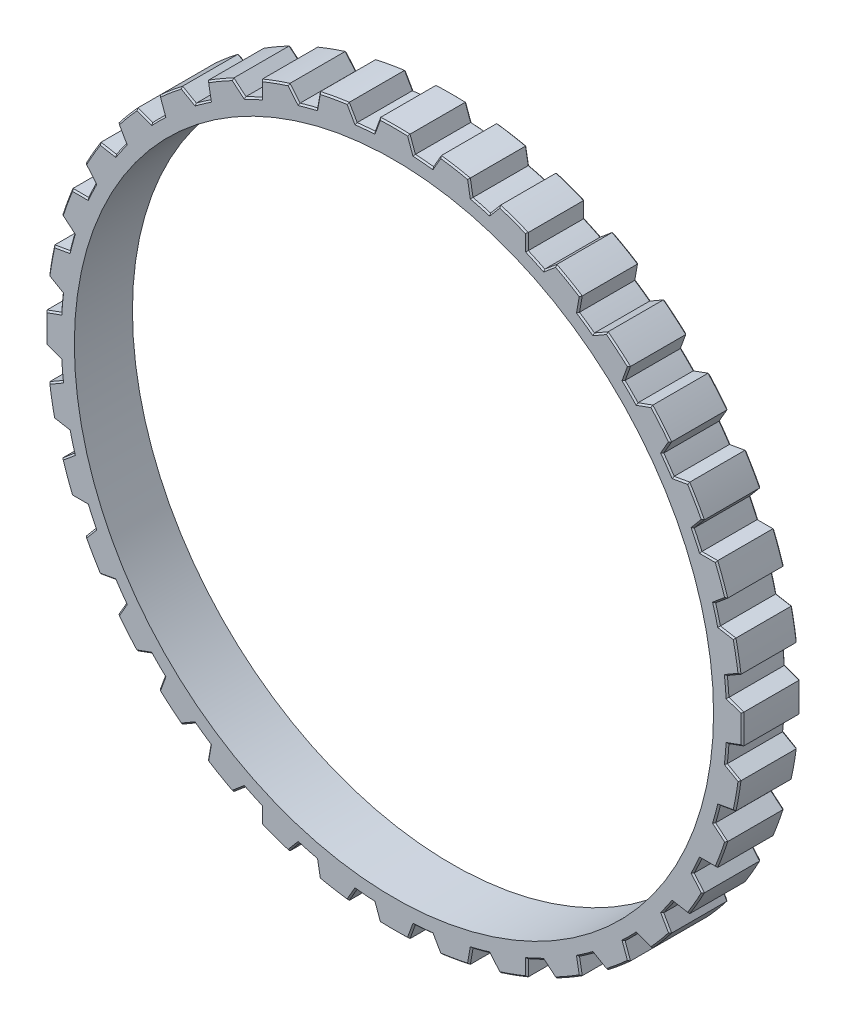
SolidWorks part; units mm, degrees
ref_plane "Płaszczyzna przednia" through (0, 0, 0) normal (0, 0, 1) x (1, 0, 0)
ref_plane "Płaszczyzna górna" through (0, 0, 0) normal (0, 1, 0) x (1, 0, 0)
ref_plane "Płaszczyzna prawa" through (0, 0, 0) normal (1, 0, 0) x (0, 0, -1)
sketch "Szkic1" plane through (0, 0, 0) normal (0, 0, 1) x (1, 0, 0)
  circle A0 centre (0, 0) radius 120
  circle A1 centre (0, 0) radius 110
  dimension "D1" = 240
  dimension "D2" = 220
extrude "Dodanie-wyciągnięcie1" add sketch "Szkic1" along normal blind 20
sketch "Szkic2" plane through (0, 0, 0) normal (0, 0, -1) x (-1, 0, 0)
  line L0 (0, 115) -> (0, 132.2478)
  line L1 (15.8574, 118.9476) -> (13.1432, 114.2465)
  line L2 (-5.0385, 119.8942) -> (-6.8952, 114.7931)
  line L3 (5.0385, 119.8942) -> (6.8952, 114.7931)
  line L4 (25.7814, 117.1978) -> (26.724, 111.8518)
  line L5 (36.2716, 114.3869) -> (32.7822, 110.2285)
  line L6 (45.7409, 110.9404) -> (45.7409, 105.512)
  line L7 (55.5836, 106.3507) -> (51.4252, 102.8613)
  line L8 (64.3106, 101.3121) -> (63.3679, 95.9662)
  line L9 (73.2068, 95.083) -> (68.5056, 92.3687)
  line L10 (80.9262, 88.6056) -> (79.0696, 83.5045)
  line L11 (88.6056, 80.9262) -> (83.5045, 79.0696)
  line L12 (95.083, 73.2068) -> (92.3687, 68.5056)
  line L13 (101.3121, 64.3106) -> (95.9662, 63.3679)
  line L14 (106.3507, 55.5836) -> (102.8613, 51.4252)
  line L15 (110.9404, 45.7409) -> (105.512, 45.7409)
  line L16 (114.3869, 36.2716) -> (110.2285, 32.7822)
  line L17 (117.1978, 25.7814) -> (111.8518, 26.724)
  line L18 (118.9476, 15.8574) -> (114.2465, 13.1432)
  line L19 (119.8942, 5.0385) -> (114.7931, 6.8952)
  line L20 (119.8942, -5.0385) -> (114.7931, -6.8952)
  line L21 (118.9476, -15.8574) -> (114.2465, -13.1432)
  line L22 (117.1978, -25.7814) -> (111.8518, -26.724)
  line L23 (114.3869, -36.2716) -> (110.2285, -32.7822)
  line L24 (110.9404, -45.7409) -> (105.512, -45.7409)
  line L25 (106.3507, -55.5836) -> (102.8613, -51.4252)
  line L26 (101.3121, -64.3106) -> (95.9662, -63.3679)
  line L27 (95.083, -73.2068) -> (92.3687, -68.5056)
  line L28 (88.6056, -80.9262) -> (83.5045, -79.0696)
  line L29 (80.9262, -88.6056) -> (79.0696, -83.5045)
  line L30 (73.2068, -95.083) -> (68.5056, -92.3687)
  line L31 (64.3106, -101.3121) -> (63.3679, -95.9662)
  line L32 (55.5836, -106.3507) -> (51.4252, -102.8613)
  line L33 (45.7409, -110.9404) -> (45.7409, -105.512)
  line L34 (36.2716, -114.3869) -> (32.7822, -110.2285)
  line L35 (25.7814, -117.1978) -> (26.724, -111.8518)
  line L36 (15.8574, -118.9476) -> (13.1432, -114.2465)
  line L37 (5.0385, -119.8942) -> (6.8952, -114.7931)
  line L38 (-5.0385, -119.8942) -> (-6.8952, -114.7931)
  line L39 (-15.8574, -118.9476) -> (-13.1432, -114.2465)
  line L40 (-25.7814, -117.1978) -> (-26.724, -111.8518)
  line L41 (-36.2716, -114.3869) -> (-32.7822, -110.2285)
  line L42 (-45.7409, -110.9404) -> (-45.7409, -105.512)
  line L43 (-55.5836, -106.3507) -> (-51.4252, -102.8613)
  line L44 (-64.3106, -101.3121) -> (-63.3679, -95.9662)
  line L45 (-73.2068, -95.083) -> (-68.5056, -92.3687)
  line L46 (-80.9262, -88.6056) -> (-79.0696, -83.5045)
  line L47 (-88.6056, -80.9262) -> (-83.5045, -79.0696)
  line L48 (-95.083, -73.2068) -> (-92.3687, -68.5056)
  line L49 (-101.3121, -64.3106) -> (-95.9662, -63.3679)
  line L50 (-106.3507, -55.5836) -> (-102.8613, -51.4252)
  line L51 (-110.9404, -45.7409) -> (-105.512, -45.7409)
  line L52 (-114.3869, -36.2716) -> (-110.2285, -32.7822)
  line L53 (-117.1978, -25.7814) -> (-111.8518, -26.724)
  line L54 (-118.9476, -15.8574) -> (-114.2465, -13.1432)
  line L55 (-119.8942, -5.0385) -> (-114.7931, -6.8952)
  line L56 (-119.8942, 5.0385) -> (-114.7931, 6.8952)
  line L57 (-118.9476, 15.8574) -> (-114.2465, 13.1432)
  line L58 (-117.1978, 25.7814) -> (-111.8518, 26.724)
  line L59 (-114.3869, 36.2716) -> (-110.2285, 32.7822)
  line L60 (-110.9404, 45.7409) -> (-105.512, 45.7409)
  line L61 (-106.3507, 55.5836) -> (-102.8613, 51.4252)
  line L62 (-101.3121, 64.3106) -> (-95.9662, 63.3679)
  line L63 (-95.083, 73.2068) -> (-92.3687, 68.5056)
  line L64 (-88.6056, 80.9262) -> (-83.5045, 79.0696)
  line L65 (-80.9262, 88.6056) -> (-79.0696, 83.5045)
  line L66 (-73.2068, 95.083) -> (-68.5056, 92.3687)
  line L67 (-64.3106, 101.3121) -> (-63.3679, 95.9662)
  line L68 (-55.5836, 106.3507) -> (-51.4252, 102.8613)
  line L69 (-45.7409, 110.9404) -> (-45.7409, 105.512)
  line L70 (-36.2716, 114.3869) -> (-32.7822, 110.2285)
  line L71 (-25.7814, 117.1978) -> (-26.724, 111.8518)
  line L72 (-15.8574, 118.9476) -> (-13.1432, 114.2465)
  circle A0 centre (0, 0) radius 115
  circle A1 centre (0, 0) radius 120
  point P153 (0, 0)
  circle M5 centre (0, 0) radius 120
  dimension "D1" = 230
  dimension "D2" = 20
  dimension "D3" = 20
  dimension "D4" = 36
extrude "Wytnij-wyciągnięcie2" cut sketch "Szkic2" against normal through all contours A0 L57 L56 M5 | A0 L55 L54 M5 | A0 L53 L52 M5 | A0 L51 L50 M5 | A0 L49 L48 M5 | A0 L47 L46 M5 | A0 L45 L44 M5 | A0 L43 L42 M5 | A0 L41 L40 M5 | A0 L39 L38 M5 | A0 L37 L36 M5 | A0 L35 L34 M5 | A0 L33 L32 M5 | A0 L31 L30 M5 | A0 L29 L28 M5 | A0 L27 L26 M5 | A0 L25 L24 M5 | A0 L23 L22 M5 | A0 L21 L20 M5 | A0 L19 L18 M5 | A0 L17 L16 M5 | A0 L15 L14 M5 | A0 L13 L12 M5 | A0 L2 L72 M5 | A0 L1 L3 M5 | A0 L5 L4 M5 | A0 L7 L6 M5 | A0 L9 L8 M5 | A0 L11 L10 M5 | A0 L59 L58 M5 | A0 L61 L60 M5 | A0 L63 L62 M5 | A0 L65 L64 M5 | A0 L67 L66 M5 | A0 L69 L68 M5 | A0 L71 L70 M5
chamfer "Sfazowanie1" distance 0.5 angle 45 288 edges at (-112.3077, -34.5269, 0) (-112.7631, -41.0424, 0) (-108.2262, -45.7409, 0) (-104.2254, -48.6011, 0) (-104.606, -53.5044, 0) (-103.923, -60, 0) (-98.6392, -63.8393, 0) (-94.2025, -65.9613, 0) (-93.7259, -70.8562, 0) (-91.9253, -77.1345, 0) (-86.055, -79.9979, 0) (-81.3173, -81.3173, 0) (-79.9979, -86.055, 0) (-77.1345, -91.9253, 0) (-70.8562, -93.7259, 0) (-65.9613, -94.2025, 0) (-63.8393, -98.6392, 0) (-60, -103.923, 0) (-53.5044, -104.606, 0) (-48.6011, -104.2254, 0) (-45.7409, -108.2262, 0) (-41.0424, -112.7631, 0) (-34.5269, -112.3077, 0) (-29.7642, -111.0815, 0) (-26.2527, -114.5248, 0) (-20.8378, -118.1769, 0) (-14.5003, -116.5971, 0) (-10.0229, -114.5624, 0) (-5.9668, -117.3436, 0) (0, -120, 0) (5.9668, -117.3436, 0) (10.0229, -114.5624, 0) (14.5003, -116.5971, 0) (20.8378, -118.1769, 0) (26.2527, -114.5248, 0) (29.7642, -111.0815, 0) (34.5269, -112.3077, 0) (41.0424, -112.7631, 0) (45.7409, -108.2262, 0) (48.6011, -104.2254, 0) (53.5044, -104.606, 0) (60, -103.923, 0) (63.8393, -98.6392, 0) (65.9613, -94.2025, 0) (70.8562, -93.7259, 0) (77.1345, -91.9253, 0) (79.9979, -86.055, 0) (81.3173, -81.3173, 0) (86.055, -79.9979, 0) (91.9253, -77.1345, 0) (93.7259, -70.8562, 0) (94.2025, -65.9613, 0) (98.6392, -63.8393, 0) (103.923, -60, 0) (104.606, -53.5044, 0) (104.2254, -48.6011, 0) (108.2262, -45.7409, 0) (112.7631, -41.0424, 0) (112.3077, -34.5269, 0) (111.0815, -29.7642, 0) (114.5248, -26.2527, 0) (118.1769, -20.8378, 0) (116.5971, -14.5003, 0) (114.5624, -10.0229, 0) (117.3436, -5.9668, 0) (120, 0, 0) (117.3436, 5.9668, 0) (114.5624, 10.0229, 0) (116.5971, 14.5003, 0) (118.1769, 20.8378, 0) (114.5248, 26.2527, 0) (111.0815, 29.7642, 0) (112.3077, 34.5269, 0) (112.7631, 41.0424, 0) (108.2262, 45.7409, 0) (104.2254, 48.6011, 0) (104.606, 53.5044, 0) (103.923, 60, 0) (98.6392, 63.8393, 0) (94.2025, 65.9613, 0) (93.7259, 70.8562, 0) (91.9253, 77.1345, 0) (86.055, 79.9979, 0) (81.3173, 81.3173, 0) (79.9979, 86.055, 0) (77.1345, 91.9253, 0) (70.8562, 93.7259, 0) (65.9613, 94.2025, 0) (63.8393, 98.6392, 0) (60, 103.923, 0) (53.5044, 104.606, 0) (48.6011, 104.2254, 0) (45.7409, 108.2262, 0) (41.0424, 112.7631, 0) (34.5269, 112.3077, 0) (29.7642, 111.0815, 0) (26.2527, 114.5248, 0) (20.8378, 118.1769, 0) (14.5003, 116.5971, 0) (10.0229, 114.5624, 0) (5.9668, 117.3436, 0) (0, 120, 0) (-5.9668, 117.3436, 0) (-10.0229, 114.5624, 0) (-14.5003, 116.5971, 0) (-20.8378, 118.1769, 0) (-26.2527, 114.5248, 0) (-29.7642, 111.0815, 0) (-34.5269, 112.3077, 0) (-41.0424, 112.7631, 0) (-45.7409, 108.2262, 0) (-48.6011, 104.2254, 0) (-53.5044, 104.606, 0) (-60, 103.923, 0) (-63.8393, 98.6392, 0) (-65.9613, 94.2025, 0) (-70.8562, 93.7259, 0) (-77.1345, 91.9253, 0) (-79.9979, 86.055, 0) (-81.3173, 81.3173, 0) (-86.055, 79.9979, 0) (-91.9253, 77.1345, 0) (-93.7259, 70.8562, 0) (-94.2025, 65.9613, 0) (-98.6392, 63.8393, 0) (-103.923, 60, 0) (-104.606, 53.5044, 0) (-104.2254, 48.6011, 0) (-108.2262, 45.7409, 0) (-112.7631, 41.0424, 0) (-112.3077, 34.5269, 0) (-111.0815, 29.7642, 0) (-114.5248, 26.2527, 0) (-118.1769, 20.8378, 0) (-116.5971, 14.5003, 0) (-114.5624, 10.0229, 0) (-117.3436, 5.9668, 0) (-120, 0, 0) (-117.3436, -5.9668, 0) (-114.5624, -10.0229, 0) (-116.5971, -14.5003, 0) (-118.1769, -20.8378, 0) (-114.5248, -26.2527, 0) (-111.0815, -29.7642, 0) (-118.1769, -20.8378, 20) (-116.5971, -14.5003, 20) (-114.5624, -10.0229, 20) (-117.3436, -5.9668, 20) (-120, 0, 20) (-117.3436, 5.9668, 20) (-114.5624, 10.0229, 20) (-116.5971, 14.5003, 20) (-118.1769, 20.8378, 20) (-114.5248, 26.2527, 20) (-111.0815, 29.7642, 20) (-112.3077, 34.5269, 20) (-112.7631, 41.0424, 20) (-108.2262, 45.7409, 20) (-104.2254, 48.6011, 20) (-104.606, 53.5044, 20) (-103.923, 60, 20) (-98.6392, 63.8393, 20) (-94.2025, 65.9613, 20) (-93.7259, 70.8562, 20) (-91.9253, 77.1345, 20) (-86.055, 79.9979, 20) (-81.3173, 81.3173, 20) (-79.9979, 86.055, 20) (-77.1345, 91.9253, 20) (-70.8562, 93.7259, 20) (-65.9613, 94.2025, 20) (-63.8393, 98.6392, 20) (-60, 103.923, 20) (-53.5044, 104.606, 20) (-48.6011, 104.2254, 20) (-45.7409, 108.2262, 20) (-41.0424, 112.7631, 20) (-34.5269, 112.3077, 20) (-29.7642, 111.0815, 20) (-26.2527, 114.5248, 20) (-20.8378, 118.1769, 20) (-14.5003, 116.5971, 20) (-10.0229, 114.5624, 20) (-5.9668, 117.3436, 20) (0, 120, 20) (5.9668, 117.3436, 20) (10.0229, 114.5624, 20) (14.5003, 116.5971, 20) (20.8378, 118.1769, 20) (26.2527, 114.5248, 20) (29.7642, 111.0815, 20) (34.5269, 112.3077, 20) (41.0424, 112.7631, 20) (45.7409, 108.2262, 20) (48.6011, 104.2254, 20) (53.5044, 104.606, 20) (60, 103.923, 20) (63.8393, 98.6392, 20) (65.9613, 94.2025, 20) (70.8562, 93.7259, 20) (77.1345, 91.9253, 20) (79.9979, 86.055, 20) (81.3173, 81.3173, 20) (86.055, 79.9979, 20) (91.9253, 77.1345, 20) (93.7259, 70.8562, 20) (94.2025, 65.9613, 20) (98.6392, 63.8393, 20) (103.923, 60, 20) (104.606, 53.5044, 20) (104.2254, 48.6011, 20) (108.2262, 45.7409, 20) (112.7631, 41.0424, 20) (112.3077, 34.5269, 20) (111.0815, 29.7642, 20) (114.5248, 26.2527, 20) (118.1769, 20.8378, 20) (116.5971, 14.5003, 20) (114.5624, 10.0229, 20) (117.3436, 5.9668, 20) (120, 0, 20) (117.3436, -5.9668, 20) (114.5624, -10.0229, 20) (116.5971, -14.5003, 20) (118.1769, -20.8378, 20) (114.5248, -26.2527, 20) (111.0815, -29.7642, 20) (112.3077, -34.5269, 20) (112.7631, -41.0424, 20) (108.2262, -45.7409, 20) (104.2254, -48.6011, 20) (104.606, -53.5044, 20) (103.923, -60, 20) (98.6392, -63.8393, 20) (94.2025, -65.9613, 20) (93.7259, -70.8562, 20) (91.9253, -77.1345, 20) (86.055, -79.9979, 20) (81.3173, -81.3173, 20) (79.9979, -86.055, 20) (77.1345, -91.9253, 20) (70.8562, -93.7259, 20) (65.9613, -94.2025, 20) (63.8393, -98.6392, 20) (60, -103.923, 20) (53.5044, -104.606, 20) (48.6011, -104.2254, 20) (45.7409, -108.2262, 20) (41.0424, -112.7631, 20) (34.5269, -112.3077, 20) (29.7642, -111.0815, 20) (26.2527, -114.5248, 20) (20.8378, -118.1769, 20) (14.5003, -116.5971, 20) (10.0229, -114.5624, 20) (5.9668, -117.3436, 20) (0, -120, 20) (-5.9668, -117.3436, 20) (-10.0229, -114.5624, 20) (-14.5003, -116.5971, 20) (-20.8378, -118.1769, 20) (-26.2527, -114.5248, 20) (-29.7642, -111.0815, 20) (-34.5269, -112.3077, 20) (-41.0424, -112.7631, 20) (-45.7409, -108.2262, 20) (-48.6011, -104.2254, 20) (-53.5044, -104.606, 20) (-60, -103.923, 20) (-63.8393, -98.6392, 20) (-65.9613, -94.2025, 20) (-70.8562, -93.7259, 20) (-77.1345, -91.9253, 20) (-79.9979, -86.055, 20) (-81.3173, -81.3173, 20) (-86.055, -79.9979, 20) (-91.9253, -77.1345, 20) (-93.7259, -70.8562, 20) (-94.2025, -65.9613, 20) (-98.6392, -63.8393, 20) (-103.923, -60, 20) (-104.606, -53.5044, 20) (-104.2254, -48.6011, 20) (-108.2262, -45.7409, 20) (-112.7631, -41.0424, 20) (-112.3077, -34.5269, 20) (-111.0815, -29.7642, 20) (-114.5248, -26.2527, 20)
